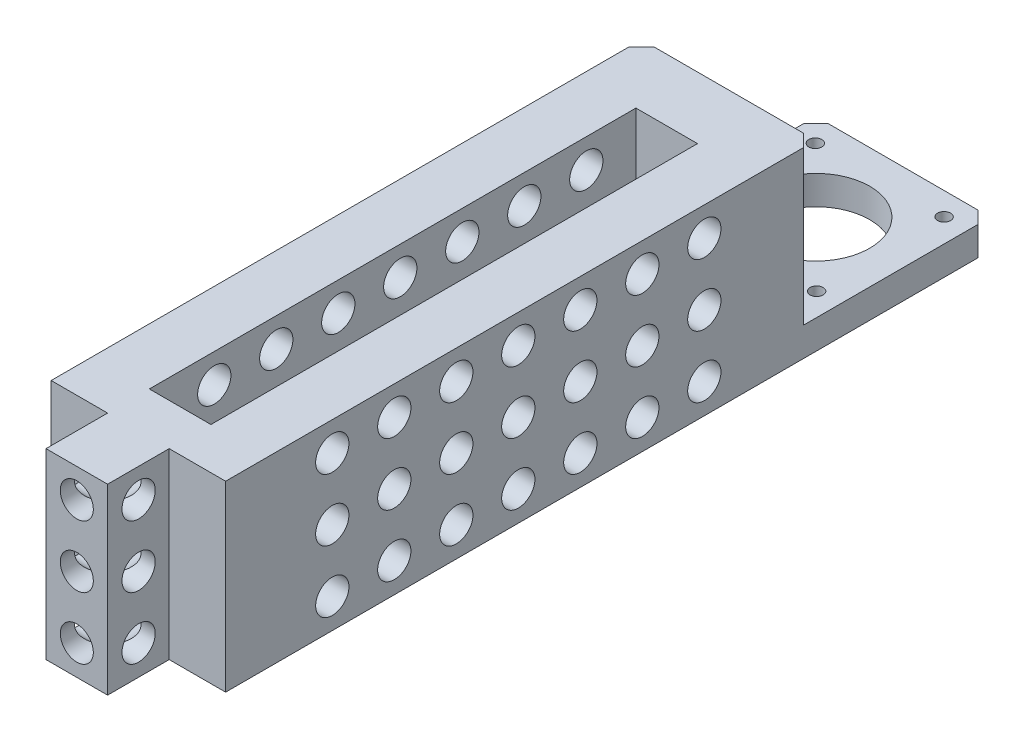
SolidWorks part; units mm, degrees
ref_plane "Front Plane" through (0, 0, 0) normal (0, 0, 1) x (1, 0, 0)
ref_plane "Top Plane" through (0, 0, 0) normal (0, 1, 0) x (1, 0, 0)
ref_plane "Right Plane" through (0, 0, 0) normal (1, 0, 0) x (0, 0, -1)
sketch "Sketch1" plane through (0, 0, 0) normal (0, 1, 0) x (1, 0, 0)
  line L0 (0, 0) -> (-42.2, 0)
  line L1 (-42.2, 0) -> (-42.2, -185)
  line L2 (-42.2, -185) -> (-28.55, -185)
  line L3 (-28.55, -185) -> (-28.55, -199.9)
  line L4 (-28.55, -199.9) -> (-13.65, -199.9)
  line L5 (-13.65, -199.9) -> (-13.65, -185)
  line L6 (-13.65, -185) -> (0, -185)
  line L7 (0, -185) -> (0, 0)
  line L8 (-28.55, -174.9) -> (-13.65, -174.9)
  line L9 (-13.65, -174.9) -> (-13.65, -57.2)
  line L10 (-13.65, -57.2) -> (-28.55, -57.2)
  line L11 (-28.55, -57.2) -> (-28.55, -174.9)
  dimension "D1" = 42.2
  dimension "D2" = 57.2
  dimension "D3" = 185
  dimension "D4" = 14.9
  dimension "D5" = 25
  dimension "D6" = 14.9
extrude "Boss-Extrude1" add sketch "Sketch1" along normal blind 44.2
sketch "Sketch2" plane through (0, 44.2, 0) normal (0, 1, 0) x (1, 0, 0)
  line L0 (-42.2, 0) -> (0, 0)
  line L1 (0, 0) -> (0, -42.2)
  line L2 (0, -185) -> (0, 0) construction
  line L3 (0, -42.2) -> (-42.2, -42.2)
  line L4 (-42.2, 0) -> (-42.2, -185) construction
  line L5 (-42.2, -42.2) -> (-42.2, 0)
  dimension "D1" = 42.2
extrude "Cut-Extrude1" cut sketch "Sketch2" against normal blind 37.2
sketch "Sketch3" plane through (0, 0, 0) normal (0, -1, 0) x (1, 0, 0)
  line L2 (0, 0) -> (-42.2, 0) construction
  line L3 (-42.2, 0) -> (-42.2, 185) construction
  line L4 (-36.6807, 5.6807) -> (-5.5193, 36.5193) construction
  circle A0 centre (-21.1, 21.1) radius 13
  circle A1 centre (-36.5193, 36.6807) radius 1.575
  circle A2 centre (-5.5193, 36.5193) radius 1.575
  circle A3 centre (-5.6807, 5.5193) radius 1.575
  circle A4 centre (-36.6807, 5.6807) radius 1.575
  circle A5 centre (-21.1, 50) radius 4.1
  circle A6 centre (-5.6, 50) radius 4.1
  circle A7 centre (-36.6, 50) radius 4.1
  point P13 (-21.1, 21.1)
  dimension "D5" = 26
  dimension "D6" = 3.15
  dimension "D8" = 8.2
  dimension "D2" = 21.1
  dimension "D3" = 21.1
  dimension "D4" = 31
  dimension "D7" = 50
  dimension "D9" = 21.1
  dimension "D10" = 2
  dimension "D11" = 2
  dimension "D1" = 4
extrude "Cut-Extrude2" cut sketch "Sketch3" against normal blind 30
sketch "Sketch5" plane through (0, 0, 0) normal (1, 0, 0) x (0, 0, -1)
  line L0 (-185, 44.2) -> (-42.2, 44.2) construction
  line L1 (-42.2, 7) -> (-42.2, 44.2) construction
  line L3 (-199.9, 44.2) -> (-199.9, 0) construction
  circle A0 centre (-69.2, 37.2) radius 4.025
  circle A1 centre (-84.2, 37.2) radius 4.025
  circle A2 centre (-99.2, 37.2) radius 4.025
  circle A3 centre (-114.2, 37.2) radius 4.025
  circle A4 centre (-84.2, 22.2) radius 4.025
  circle A5 centre (-99.2, 22.2) radius 4.025
  circle A6 centre (-114.2, 22.2) radius 4.025
  circle A7 centre (-84.2, 7.2) radius 4.025
  circle A8 centre (-99.2, 7.2) radius 4.025
  circle A9 centre (-114.2, 7.2) radius 4.025
  circle A10 centre (-69.2, 22.2) radius 4.025
  circle A11 centre (-69.2, 7.2) radius 4.025
  circle A12 centre (-192.4, 37.2) radius 4.025
  circle A13 centre (-192.4, 22.2) radius 4.025
  circle A14 centre (-192.4, 7.2) radius 4.025
  circle A15 centre (-129.2, 37.2) radius 4.025
  circle A16 centre (-144.2, 37.2) radius 4.025
  circle A17 centre (-159.2, 37.2) radius 4.025
  circle A18 centre (-129.2, 22.2) radius 4.025
  circle A19 centre (-144.2, 22.2) radius 4.025
  circle A20 centre (-159.2, 22.2) radius 4.025
  circle A21 centre (-129.2, 7.2) radius 4.025
  circle A22 centre (-144.2, 7.2) radius 4.025
  circle A23 centre (-159.2, 7.2) radius 4.025
  dimension "D1" = 8.05
  dimension "D6" = 8.05
  dimension "D2" = 7
  dimension "D3" = 27
  dimension "D7" = 7.5
  dimension "D8" = 7
  dimension "D4" = 7
  dimension "D5" = 3
  dimension "D9" = 3
extrude "Cut-Extrude3" cut sketch "Sketch5" against normal blind 55
sketch "Sketch6" plane through (0, 0, 199.9) normal (0, 0, 1) x (1, 0, 0)
  line L0 (-28.55, 44.2) -> (-13.65, 44.2) construction
  line L1 (0, 44.2) -> (0, 0) construction
  circle A0 centre (-21.1, 37.2) radius 4
  circle A1 centre (-21.1, 22.2) radius 4
  circle A2 centre (-21.1, 7.2) radius 4
  dimension "D1" = 8
  dimension "D2" = 7
  dimension "D3" = 21.1
  dimension "D4" = 3
extrude "Cut-Extrude4" cut sketch "Sketch6" against normal blind 25
chamfer "Chamfer1" distance 3 angle 45 4 edges at (-42.2, 3.5, 0) (0, 3.5, 0) (-42.2, 25.6, 42.2) (0, 25.6, 42.2)
